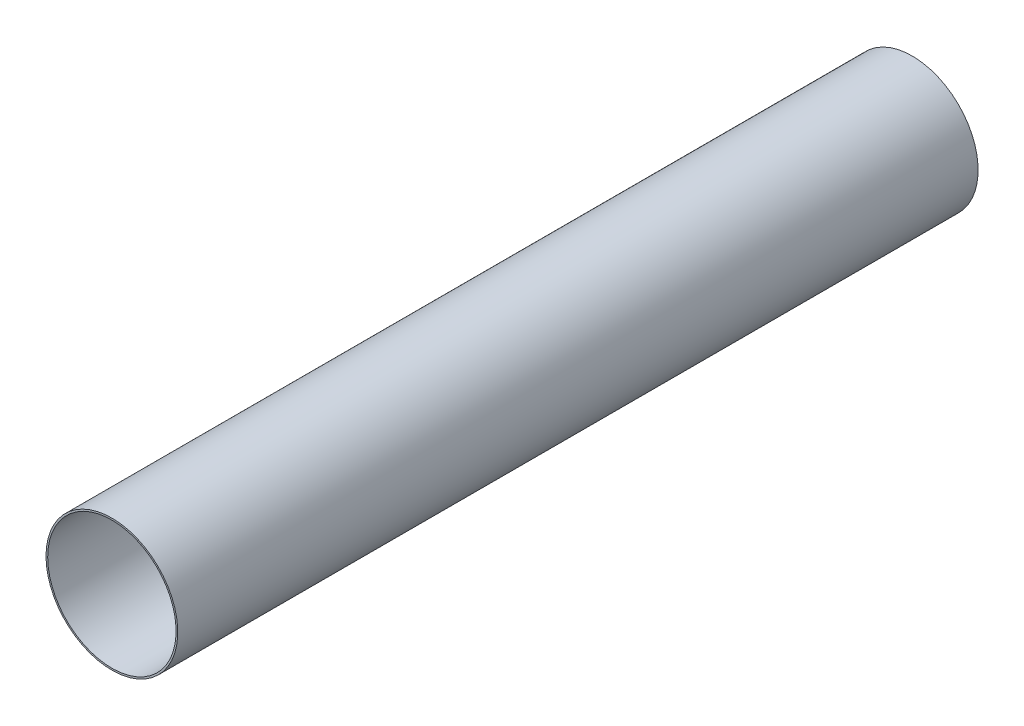
SolidWorks part; units mm, degrees
material "E-Glass Fiber"
ref_plane "Front" through (0, 0, 0) normal (0, 0, 1) x (1, 0, 0)
ref_plane "Top" through (0, 0, 0) normal (0, 1, 0) x (1, 0, 0)
ref_plane "Right" through (0, 0, 0) normal (1, 0, 0) x (0, 0, -1)
sketch "Sketch1" plane through (0, 0, 0) normal (0, 0, 1) x (1, 0, 0)
  circle A0 centre (0, 0) radius 78.2
  circle A1 centre (0, 0) radius 76.2
  dimension "D1" = 156.4
  dimension "D2" = 152.4
extrude "Boss-Extrude1" add sketch "Sketch1" along normal blind 950
